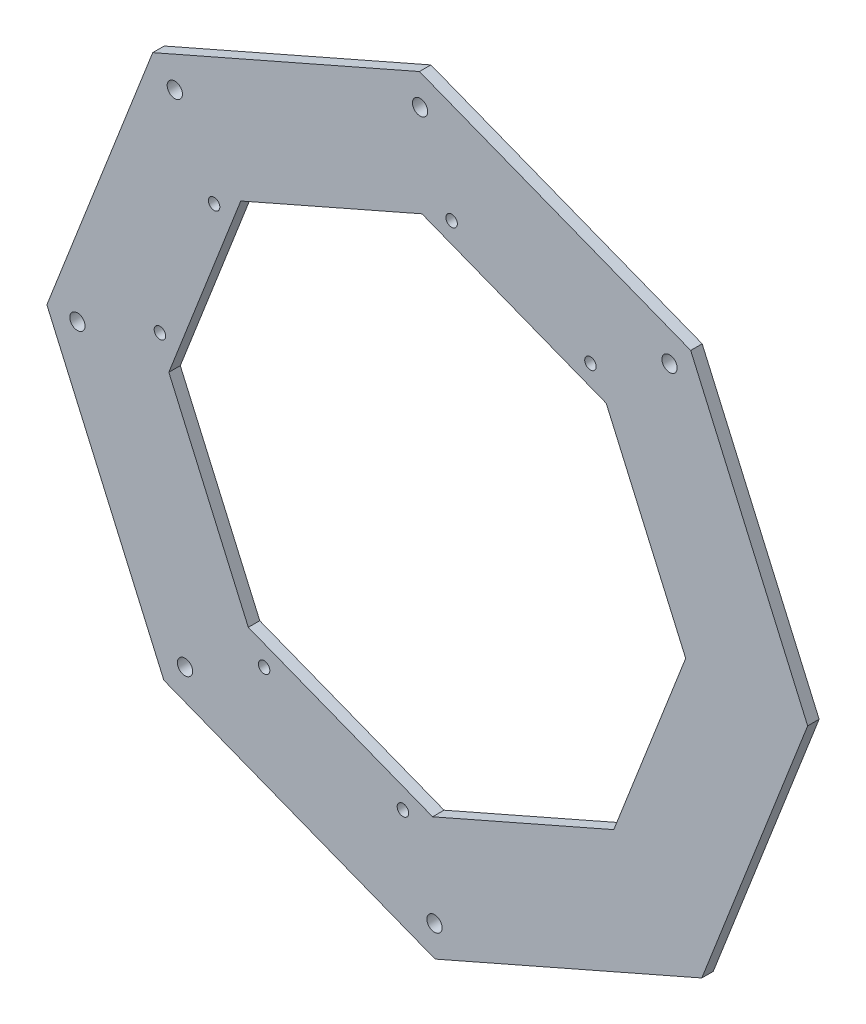
SolidWorks part; units mm, degrees
ref_plane "Alzado" through (0, 0, 0) normal (0, 0, 1) x (1, 0, 0)
ref_plane "Planta" through (0, 0, 0) normal (0, 1, 0) x (1, 0, 0)
ref_plane "Vista lateral" through (0, 0, 0) normal (1, 0, 0) x (0, 0, -1)
sketch "Croquis1" plane through (0, 0, 0) normal (0, 0, 1) x (1, 0, 0)
  line L1 (-99.5589, -2.0527) -> (-68.9473, -71.8502)
  line L2 (-68.9473, -71.8502) -> (2.0527, -99.5589)
  line L3 (2.0527, -99.5589) -> (71.8502, -68.9473)
  line L4 (71.8502, -68.9473) -> (99.5589, 2.0527)
  line L5 (99.5589, 2.0527) -> (68.9473, 71.8502)
  line L6 (68.9473, 71.8502) -> (-2.0527, 99.5589)
  line L7 (-2.0527, 99.5589) -> (-71.8502, 68.9473)
  line L8 (-71.8502, 68.9473) -> (-99.5589, -2.0527)
  circle A1 centre (0, 0) radius 92 construction
  dimension "D1" = 184
  dimension "D2" = 71
extrude "Saliente-Extruir1" add sketch "Croquis1" along normal blind 3
sketch "Croquis2" plane through (0, 0, 3) normal (0, 0, 1) x (1, 0, 0)
  line L0 (0, 0) -> (24.5402, 62.8811) construction
  line L1 (-67.6351, -1.3945) -> (-46.8392, -48.8113)
  line L2 (-46.8392, -48.8113) -> (1.3945, -67.6351)
  line L3 (1.3945, -67.6351) -> (48.8113, -46.8392)
  line L4 (48.8113, -46.8392) -> (67.6351, 1.3945)
  line L5 (67.6351, 1.3945) -> (46.8392, 48.8113)
  line L6 (46.8392, 48.8113) -> (-1.3945, 67.6351)
  line L7 (-1.3945, 67.6351) -> (-48.8113, 46.8392)
  line L8 (-48.8113, 46.8392) -> (-67.6351, -1.3945)
  line L10 (68.9473, 71.8502) -> (-2.0527, 99.5589) construction
  line L11 (24.5402, 62.8811) -> (6.3745, 69.9705) construction
  line L12 (0, 0) -> (85.7046, -33.4473) construction
  line L13 (71.8502, -68.9473) -> (99.5589, 2.0527) construction
  line L14 (0, 0) -> (-62.8811, 24.5402) construction
  line L15 (-62.8811, 24.5402) -> (-69.9705, 6.3745) construction
  line L16 (-71.8502, 68.9473) -> (-99.5589, -2.0527) construction
  circle A0 centre (0, 0) radius 62.5 construction
  circle A1 centre (6.3745, 69.9705) radius 1.5
  circle A2 centre (42.7058, 55.7917) radius 1.5
  circle A3 centre (-6.3745, -69.9705) radius 1.5
  circle A4 centre (-42.7058, -55.7917) radius 1.5
  circle A5 centre (-69.9705, 6.3745) radius 1.5
  circle A6 centre (-55.7917, 42.7058) radius 1.5
  dimension "D1" = 125
  dimension "D2" = 3
  dimension "D6" = 24.5
  dimension "D9" = 3
  dimension "D11" = 24.5
  dimension "D3" = 67.5
  dimension "D4" = 90
  dimension "D5" = 19.5
  dimension "D7" = 67.5
  dimension "D8" = 19.5
  dimension "D10" = 90
extrude "Cortar-Extruir1" cut sketch "Croquis2" against normal through all
sketch "Croquis3" plane through (0, 0, 3) normal (0, 0, 1) x (1, 0, 0)
  line L0 (68.9473, 71.8502) -> (-2.0527, 99.5589) construction
  line L1 (-2.0527, 99.5589) -> (-1.8878, 91.5606) construction
  circle A0 centre (-1.8878, 91.5606) radius 2
  circle A1 centre (63.4083, 66.078) radius 2
  circle A4 centre (1.8878, -91.5606) radius 2
  circle A5 centre (-63.4083, -66.078) radius 2
  circle A6 centre (-91.5606, -1.8878) radius 2
  circle A7 centre (-66.078, 63.4083) radius 2
  circle A8 centre (91.5606, 1.8878) radius 2 [skipped]
  circle A9 centre (66.078, -63.4083) radius 2 [skipped]
  point P24 (0, 0)
  dimension "D1" = 4
  dimension "D2" = 7.391
  dimension "D3" = 7.9983
  dimension "D4" = 8
extrude "Cortar-Extruir2" cut sketch "Croquis3" against normal through all
